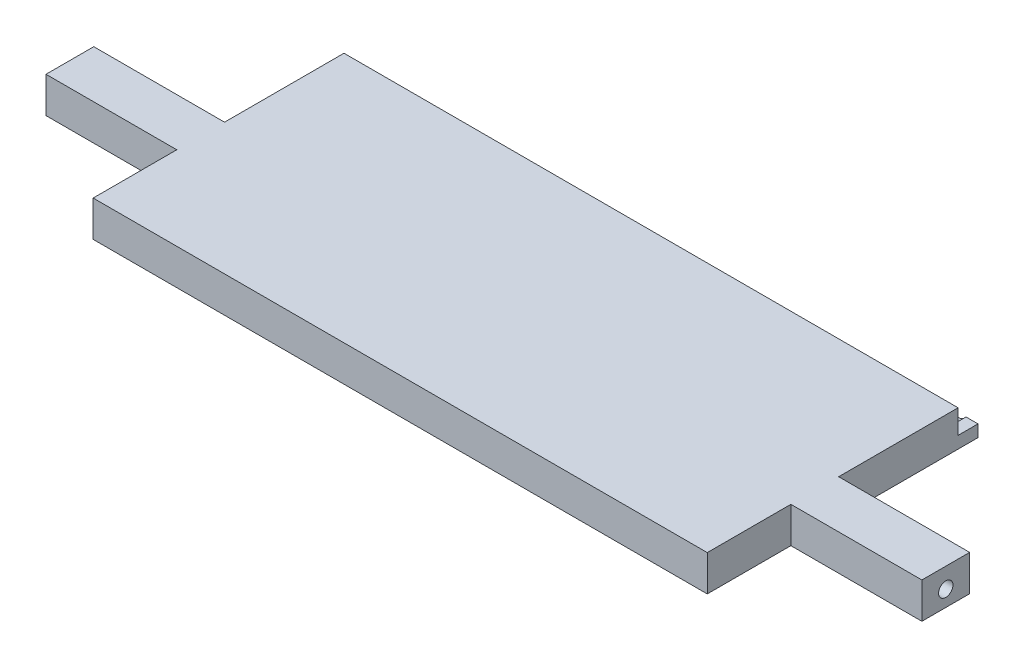
SolidWorks part; units mm, degrees
ref_plane "Спереди" through (0, 0, 0) normal (0, 0, 1) x (1, 0, 0)
ref_plane "Сверху" through (0, 0, 0) normal (0, 1, 0) x (1, 0, 0)
ref_plane "Справа" through (0, 0, 0) normal (1, 0, 0) x (0, 0, -1)
sketch "Эскиз1" plane through (0, 0, 0) normal (0, 0, 1) x (1, 0, 0)
  line L0 (-1000, 4.5) -> (49000, 4.5) construction
  line L1 (0, 0) -> (220, 0)
  line L2 (0, 0) -> (0, 9)
  line L3 (0, 9) -> (220, 9)
  line L4 (220, 0) -> (220, 9)
  circle A0 centre (37.97, 4.5) radius 2.6
  circle A9 centre (55.97, 4.5) radius 2.6
  circle A10 centre (73.97, 4.5) radius 2.6
  circle A11 centre (91.97, 4.5) radius 2.6
  circle A12 centre (109.97, 4.5) radius 2.6
  circle A13 centre (127.97, 4.5) radius 2.6
  circle A14 centre (145.97, 4.5) radius 2.6
  circle A15 centre (163.97, 4.5) radius 2.6
  circle A16 centre (181.97, 4.5) radius 2.6
  point P26 (0, 4.5)
  dimension "D3" = 5.2
  dimension "D6" = 38.03
  dimension "D7" = 12.8
  dimension "D8" = 18
  dimension "D1" = 4.5
  dimension "D2" = 220
  dimension "D4" = 37.97
  dimension "D5" = 9
extrude "Бобышка-Вытянуть1" add sketch "Эскиз1" along normal blind 65
sketch "Эскиз2" plane through (0, 9, 0) normal (0, 1, 0) x (1, 0, 0)
  line L0 (220, -65) -> (220, 0) construction
  line L1 (0, 0) -> (220, 0)
  line L2 (0, 0) -> (0, -5)
  line L3 (0, -5) -> (220, -5)
  line L4 (220, 0) -> (220, -5)
  dimension "D1" = 5
extrude "Вырез-Вытянуть1" cut sketch "Эскиз2" against normal blind 6
sketch "Эскиз3" plane through (0, 9, 0) normal (0, 1, 0) x (1, 0, 0)
  line L0 (220, -65) -> (0, -65) construction
  line L1 (0, 0) -> (32.8463, 0)
  line L2 (0, 0) -> (0, -35)
  line L3 (0, -35) -> (32.8463, -35)
  line L4 (32.8463, 0) -> (32.8463, -35)
  line L5 (0, -65) -> (32.8463, -65)
  line L6 (0, -65) -> (0, -47)
  line L7 (0, -47) -> (32.8463, -47)
  line L8 (32.8463, -65) -> (32.8463, -47)
  line L9 (184.0937, -5) -> (184.0937, 0) construction
  line L10 (220, 0) -> (187.0937, 0)
  line L11 (220, 0) -> (220, -35)
  line L12 (220, -35) -> (187.0937, -35)
  line L13 (187.0937, 0) -> (187.0937, -35)
  line L14 (220, -65) -> (187.0937, -65)
  line L15 (220, -65) -> (220, -47)
  line L16 (220, -47) -> (187.0937, -47)
  line L17 (187.0937, -65) -> (187.0937, -47)
  line L18 (35.8463, 0) -> (35.8463, -5) construction
  dimension "D1" = 12
  dimension "D2" = 12
  dimension "D3" = 18
  dimension "D4" = 18
  dimension "D5" = 3
  dimension "D6" = 3
  dimension "D7" = 3
  dimension "D8" = 3
extrude "Вырез-Вытянуть2" cut sketch "Эскиз3" against normal through all
sketch "Эскиз4" plane through (0, 0, 0) normal (-1, 0, 0) x (0, 0, 1)
  line L3 (47, 0) -> (35, 0) construction
  line L4 (35, 0) -> (35, 9) construction
  circle A0 centre (41, 4) radius 1.8
  dimension "D1" = 3.6
  dimension "D2" = 6
  dimension "D3" = 4
extrude "Вырез-Вытянуть3" cut sketch "Эскиз4" against normal blind 10
sketch "Эскиз5" plane through (220, 0, 0) normal (1, 0, 0) x (0, 0, -1)
  line L0 (-47, 9) -> (-35, 9) construction
  line L1 (-47, 0) -> (-47, 9) construction
  circle A0 centre (-41, 4) radius 1.8
  dimension "D1" = 3.6
  dimension "D2" = 5
  dimension "D3" = 6
extrude "Вырез-Вытянуть4" cut sketch "Эскиз5" against normal blind 10
sketch "Эскиз6" plane through (0, 0, 65) normal (0, 0, 1) x (1, 0, 0)
  line L1 (32.8463, 9) -> (187.0937, 9)
  line L2 (32.8463, 9) -> (32.8463, 0)
  line L3 (32.8463, 0) -> (187.0937, 0)
  line L4 (187.0937, 9) -> (187.0937, 0)
extrude "Бобышка-Вытянуть2" add sketch "Эскиз6" along normal blind 3
